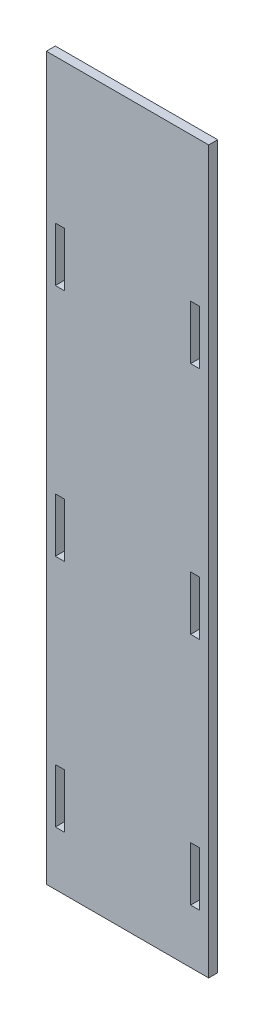
SolidWorks part; units mm, degrees
ref_plane "Front Plane" through (0, 0, 0) normal (0, 0, 1) x (1, 0, 0)
ref_plane "Top Plane" through (0, 0, 0) normal (0, 1, 0) x (1, 0, 0)
ref_plane "Right Plane" through (0, 0, 0) normal (1, 0, 0) x (0, 0, -1)
sketch "Sketch1" plane through (0, 0, 0) normal (0, 0, 1) x (1, 0, 0)
  line L0 (57.15, 254) -> (57.15, 0)
  line L1 (0, 0) -> (57.15, 0)
  line L2 (0, 254) -> (0, 0)
  line L3 (0, 254) -> (57.15, 254)
  dimension "D1" = 254
  dimension "D2" = 57.15
extrude "Boss-Extrude1" add sketch "Sketch1" along normal blind 3.175
sketch "Sketch3" plane through (0, 0, 3.175) normal (0, 0, 1) x (1, 0, 0)
  line L0 (0, 0) -> (57.15, 0) construction
  line L1 (3.175, 203.2) -> (6.35, 203.2)
  line L2 (3.175, 203.2) -> (3.175, 184.15)
  line L3 (3.175, 184.15) -> (6.35, 184.15)
  line L4 (6.35, 203.2) -> (6.35, 184.15)
  line L5 (3.175, 120.65) -> (6.35, 120.65)
  line L6 (3.175, 120.65) -> (3.175, 101.6)
  line L7 (3.175, 101.6) -> (6.35, 101.6)
  line L8 (6.35, 120.65) -> (6.35, 101.6)
  line L9 (3.175, 38.1) -> (6.35, 38.1)
  line L10 (3.175, 38.1) -> (3.175, 19.05)
  line L11 (3.175, 19.05) -> (6.35, 19.05)
  line L12 (6.35, 38.1) -> (6.35, 19.05)
  line L13 (50.8, 203.2) -> (53.975, 203.2)
  line L14 (50.8, 203.2) -> (50.8, 184.15)
  line L15 (50.8, 184.15) -> (53.975, 184.15)
  line L16 (53.975, 203.2) -> (53.975, 184.15)
  line L17 (50.8, 120.65) -> (53.975, 120.65)
  line L18 (50.8, 120.65) -> (50.8, 101.6)
  line L19 (50.8, 101.6) -> (53.975, 101.6)
  line L20 (53.975, 120.65) -> (53.975, 101.6)
  line L21 (50.8, 38.1) -> (53.975, 38.1)
  line L22 (50.8, 38.1) -> (50.8, 19.05)
  line L23 (50.8, 19.05) -> (53.975, 19.05)
  line L24 (53.975, 38.1) -> (53.975, 19.05)
  line L25 (0, 254) -> (0, 0) construction
  dimension "D1" = 19.05
  dimension "D2" = 19.05
  dimension "D3" = 63.5
  dimension "D4" = 63.5
  dimension "D5" = 44.45
  dimension "D6" = 3.175
  dimension "D7" = 6.35
extrude "Cut-Extrude1" cut sketch "Sketch3" against normal through all
